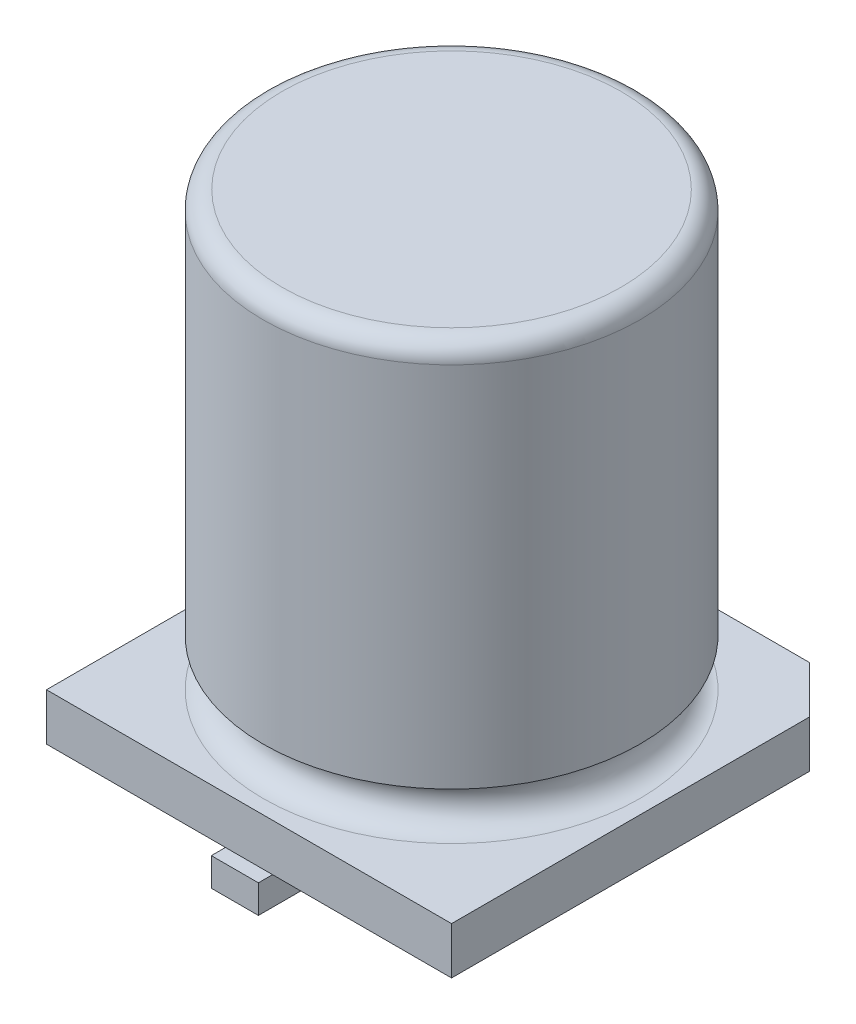
SolidWorks part; units mm, degrees
ref_plane "Front Plane" through (0, 0, 0) normal (0, 0, 1) x (1, 0, 0)
ref_plane "Top Plane" through (0, 0, 0) normal (0, 1, 0) x (1, 0, 0)
ref_plane "Right Plane" through (0, 0, 0) normal (1, 0, 0) x (0, 0, -1)
sketch "Sketch1" plane through (0, 0, 0) normal (0, 1, 0) x (1, 0, 0)
  line L0 (0, 1.858) -> (0, -2.0802) construction
  line L1 (-2.4775, 0) -> (3.1194, 0) construction
  line L2 (0.25, 0.75) -> (0.25, 2.3)
  line L3 (0.25, 2.3) -> (-0.25, 2.3)
  line L4 (-0.25, 2.3) -> (-0.25, 0.75)
  line L5 (0.25, -0.75) -> (0.25, -2.3)
  line L6 (0.25, -2.3) -> (-0.25, -2.3)
  line L7 (-0.25, -2.3) -> (-0.25, -0.75)
  arc A0 (-0.25, 0.75) -> (0.25, 0.75) centre (0, 0.75) ccw
  arc A1 (-0.25, -0.75) -> (0.25, -0.75) centre (0, -0.75) cw
  point P5 (0, 0.5)
  dimension "D1" = 0.5
  dimension "D2" = 0.5
  dimension "D3" = 0.25
  dimension "D4" = 1.55
extrude "Boss-Extrude1" add sketch "Sketch1" along normal blind 0.3
ref_plane "Plane1" through (0, 0.3, 0) normal (0, 1, 0) x (1, 0, 0)
sketch "Sketch3" plane through (0, 0.3, 0) normal (0, 1, 0) x (1, 0, 0)
  line L0 (-1.5674, 0) -> (1.6133, 0) construction
  line L1 (0, 2.6463) -> (0, -2.6856) construction
  line L2 (-2.15, -2.15) -> (2.15, -2.15)
  line L3 (2.15, -2.15) -> (2.15, 1.65)
  line L4 (2.15, 1.65) -> (1.65, 2.15)
  line L5 (1.65, 2.15) -> (-1.65, 2.15)
  line L6 (-2.15, -2.15) -> (-2.15, 1.65)
  line L7 (-2.15, 1.65) -> (-1.65, 2.15)
  point P11 (0, -2.15)
  point P13 (0, 2.15)
  dimension "D1" = 2.15
  dimension "D2" = 2.15
  dimension "D3" = 3.8
  dimension "D4" = 2.15
  dimension "D5" = 1.65
extrude "Boss-Extrude2" add sketch "Sketch3" along normal blind 0.5
sketch "Sketch4" plane through (0, 0.8, 0) normal (0, 1, 0) x (1, 0, 0)
  circle A0 centre (0, 0) radius 2
extrude "Boss-Extrude3" add sketch "Sketch4" along normal blind 4.6
fillet "Fillet1" radius 0.2 1 edges at (0, 5.4, 2)
sketch "Sketch6" plane through (0, 0, 0) normal (0, 0, 1) x (1, 0, 0)
  line L0 (0, 0) -> (0, 6.6399) construction
  line L2 (2, 0.8) -> (2, 1.05) construction
  line L3 (-2.15, 0.8) -> (2.15, 0.8) construction
  line L4 (2, 0.8) -> (2, 5.2) construction
  circle A0 centre (2, 1.05) radius 0.25
revolve "Cut-Revolve1" cut sketch "Sketch6" angle 360 about L0
